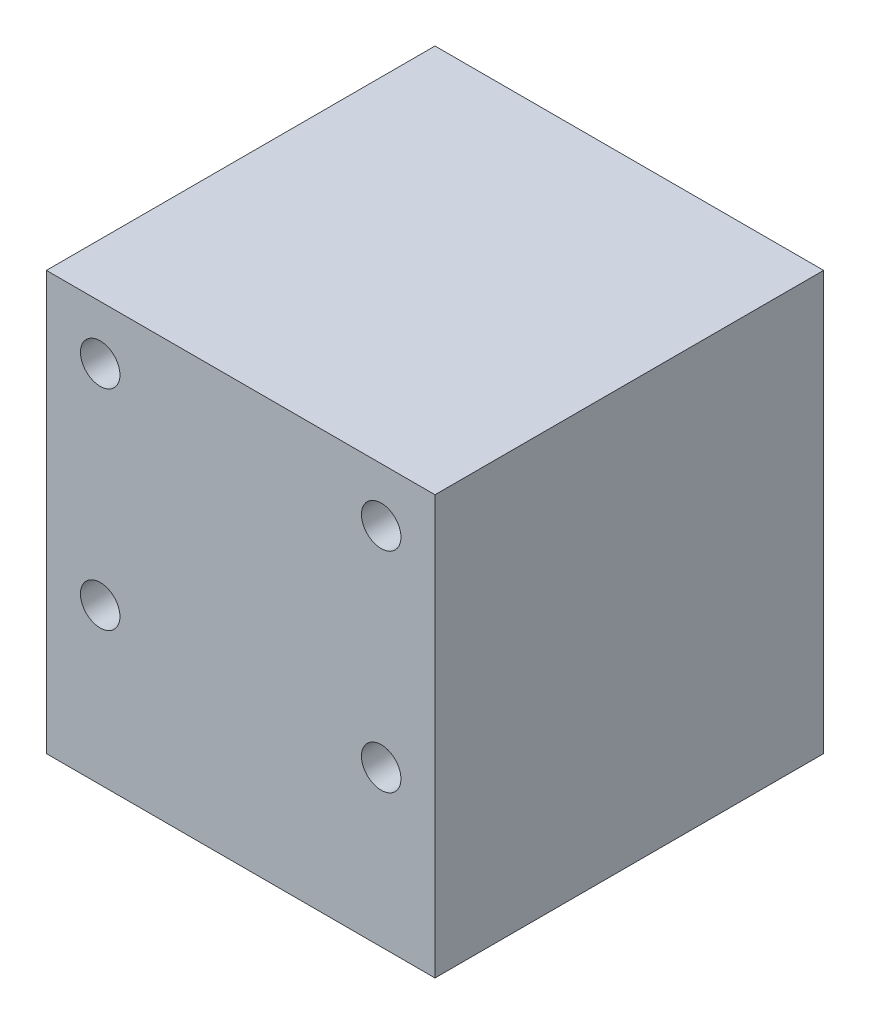
SolidWorks part; units mm, degrees
ref_plane "前视基准面" through (0, 0, 0) normal (0, 0, 1) x (1, 0, 0)
ref_plane "上视基准面" through (0, 0, 0) normal (0, 1, 0) x (1, 0, 0)
ref_plane "右视基准面" through (0, 0, 0) normal (1, 0, 0) x (0, 0, -1)
sketch "草图1" plane through (0, 0, 0) normal (0, 1, 0) x (1, 0, 0)
  line L1 (0, 0) -> (32.5, 0)
  line L2 (0, 0) -> (0, 32.5)
  line L3 (0, 32.5) -> (32.5, 32.5)
  line L4 (32.5, 0) -> (32.5, 32.5)
  dimension "D1" = 32.5
  dimension "D2" = 32.5
extrude "凸台-拉伸1" add sketch "草图1" along normal blind 35
sketch "草图2" plane through (0, 0, 0) normal (0, 0, 1) x (1, 0, 0)
  line L0 (0, 35) -> (0, 0) construction
  line L1 (0, 35) -> (32.5, 35) construction
  line L2 (4.5, 30.5) -> (28, 30.5) construction
  line L3 (4.5, 30.5) -> (4.5, 13) construction
  line L4 (4.5, 13) -> (28, 13) construction
  line L5 (28, 30.5) -> (28, 13) construction
  line L6 (32.5, 35) -> (32.5, 0) construction
  circle A0 centre (4.5, 30.5) radius 1.65
  circle A1 centre (28, 30.5) radius 1.65
  circle A2 centre (4.5, 13) radius 1.65
  circle A3 centre (28, 13) radius 1.65
  dimension "D1" = 4.5
  dimension "D2" = 4.5
  dimension "D5" = 3.3
  dimension "D6" = 23.5
  dimension "D3" = 4.5
  dimension "D4" = 17.5
extrude "切除-拉伸1" cut sketch "草图2" against normal blind 5
